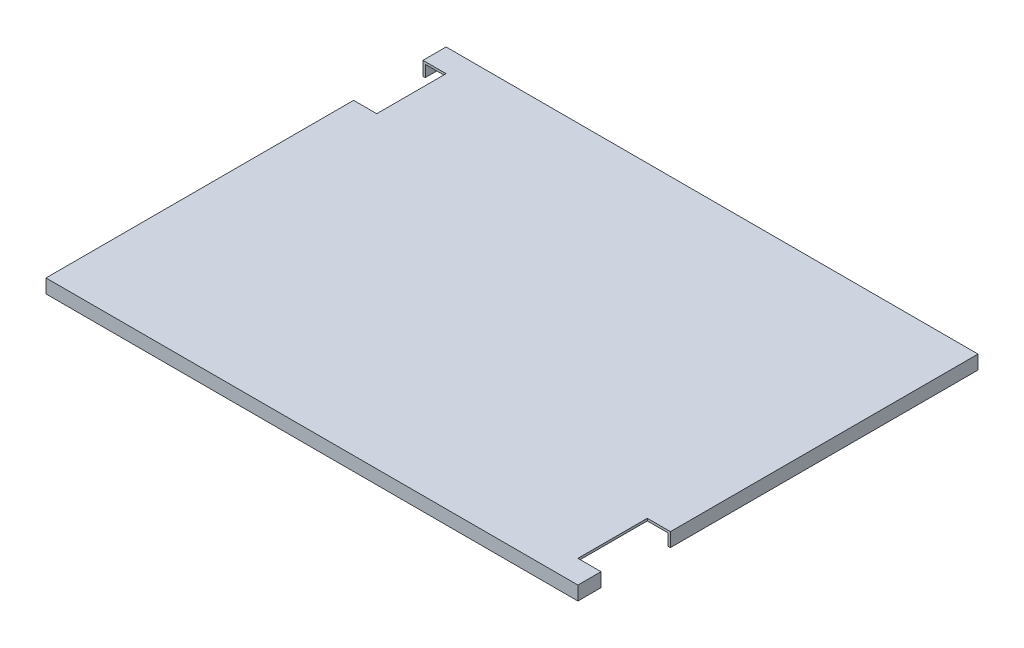
SolidWorks part; units mm, degrees
ref_plane "Front Plane" through (0, 0, 0) normal (0, 0, 1) x (1, 0, 0)
ref_plane "Top Plane" through (0, 0, 0) normal (0, 1, 0) x (1, 0, 0)
ref_plane "Right Plane" through (0, 0, 0) normal (1, 0, 0) x (0, 0, -1)
sketch "Sketch1" plane through (0, 0, 0) normal (0, 1, 0) x (1, 0, 0)
  line L1 (-115, -86.5) -> (115, -86.5)
  line L2 (-115, -86.5) -> (-115, 86.5)
  line L3 (-115, 86.5) -> (115, 86.5)
  line L4 (115, -86.5) -> (115, 86.5)
  line L5 (-115, -86.5) -> (115, 86.5) construction
  line L6 (-115, 86.5) -> (115, -86.5) construction
  point P0 (0, 0)
  dimension "D1" = 230
  dimension "D2" = 173
extrude "Boss-Extrude1" add sketch "Sketch1" along normal blind 6
sketch "Sketch2" plane through (0, 0, 0) normal (0, 1, 0) x (1, 0, 0)
  line L0 (115, 86.5) -> (-115, 86.5) construction
  line L1 (114, -85.5) -> (-114, -85.5)
  line L2 (114, -85.5) -> (114, 85.5)
  line L3 (114, 85.5) -> (-114, 85.5)
  line L4 (-114, -85.5) -> (-114, 85.5)
  line L5 (114, -85.5) -> (-114, 85.5) construction
  line L6 (114, 85.5) -> (-114, -85.5) construction
  line L7 (115, -86.5) -> (115, 86.5) construction
  point P0 (0, 0)
  dimension "D1" = 1
  dimension "D2" = 1
extrude "Cut-Extrude1" cut sketch "Sketch2" along normal blind 5
sketch "Sketch3" plane through (0, 6, 0) normal (0, 1, 0) x (1, 0, 0)
  line L0 (115, -86.5) -> (115, 86.5) construction
  line L1 (115, -76.5) -> (105, -76.5)
  line L2 (115, -76.5) -> (115, -46.5)
  line L3 (115, -46.5) -> (105, -46.5)
  line L4 (105, -76.5) -> (105, -46.5)
  line L5 (-115, -86.5) -> (115, -86.5) construction
  line L6 (-115, 86.5) -> (-115, -86.5) construction
  line L7 (-115, 76.5) -> (-105, 76.5)
  line L8 (-115, 76.5) -> (-115, 46.5)
  line L9 (-115, 46.5) -> (-105, 46.5)
  line L10 (-105, 76.5) -> (-105, 46.5)
  line L11 (115, 86.5) -> (-115, 86.5) construction
  dimension "D1" = 30
  dimension "D2" = 10
  dimension "D3" = 10
  dimension "D4" = 10
  dimension "D5" = 30
  dimension "D6" = 10
extrude "Cut-Extrude2" cut sketch "Sketch3" against normal through all
